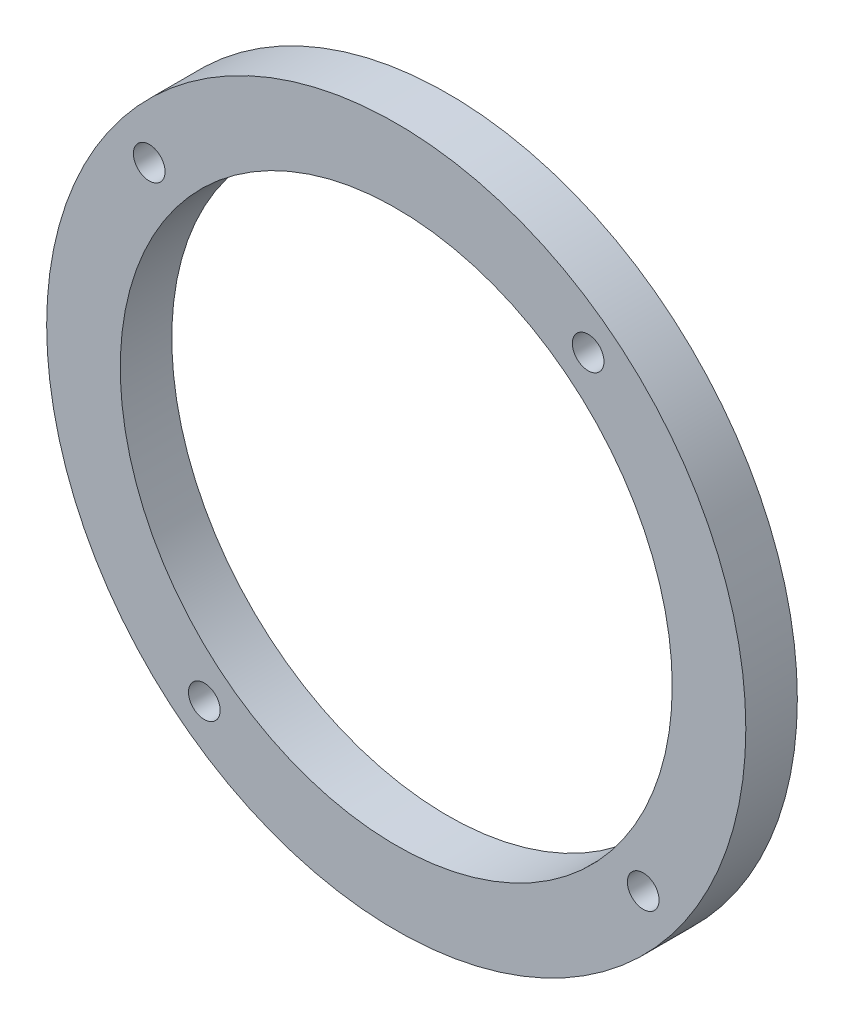
SolidWorks part; units mm, degrees
ref_plane "前视基准面" through (0, 0, 0) normal (0, 0, 1) x (1, 0, 0)
ref_plane "上视基准面" through (0, 0, 0) normal (0, 1, 0) x (1, 0, 0)
ref_plane "右视基准面" through (0, 0, 0) normal (1, 0, 0) x (0, 0, -1)
other "Configuration Table"
sketch "草图1" plane through (0, 0, 0) normal (0, 0, 1) x (1, 0, 0)
  circle A0 centre (0, 0) radius 47.5
  circle A1 centre (0, 0) radius 37.5
  dimension "D1" = 95
  dimension "D2" = 75
extrude "凸台-拉伸1" add sketch "草图1" along normal blind 7
sketch "草图2" plane through (0, 0, 7) normal (0, 0, 1) x (1, 0, 0)
  circle A0 centre (-33.5598, 26.0766) radius 2.15
  circle A1 centre (26.0766, 33.5598) radius 2.15
  circle A2 centre (33.5598, -26.0766) radius 2.15
  circle A3 centre (-26.0766, -33.5598) radius 2.15
extrude "切除-拉伸1" cut sketch "草图2" against normal up to next
